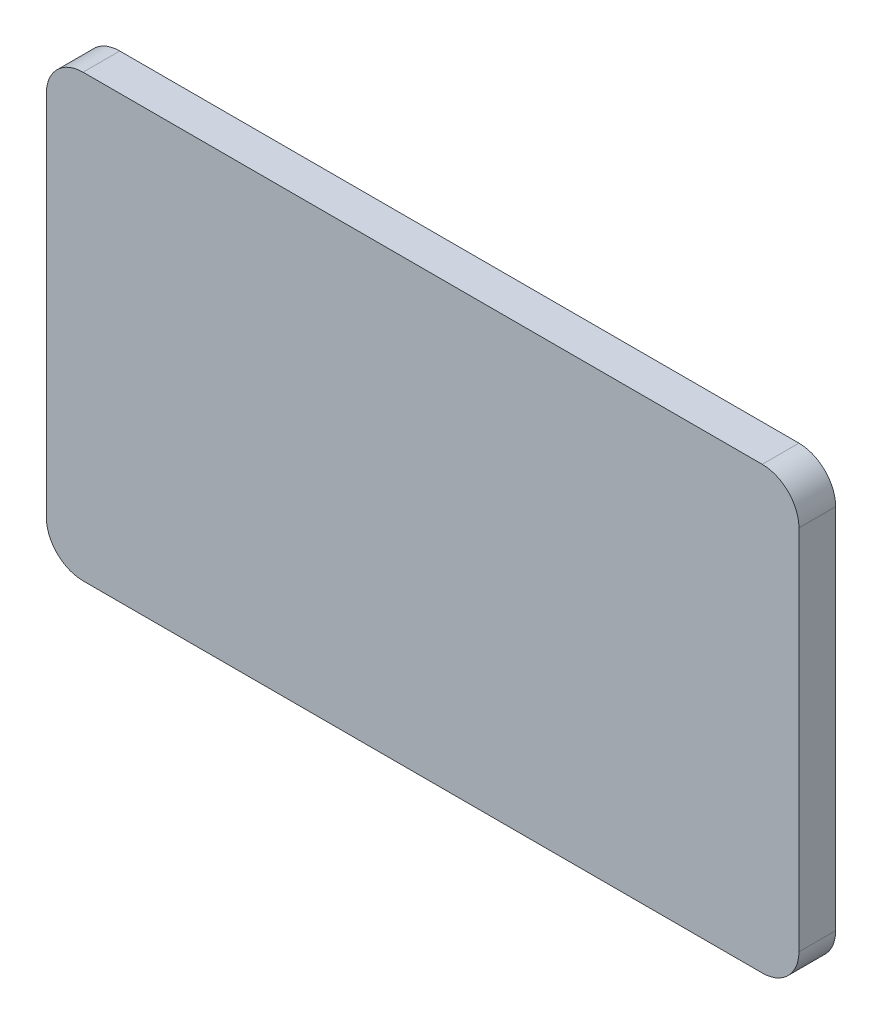
SolidWorks part; units mm, degrees
ref_plane "Front Plane" through (0, 0, 0) normal (0, 0, 1) x (1, 0, 0)
ref_plane "Top Plane" through (0, 0, 0) normal (0, 1, 0) x (1, 0, 0)
ref_plane "Right Plane" through (0, 0, 0) normal (1, 0, 0) x (0, 0, -1)
sketch "Sketch1" plane through (0, 0, 0) normal (0, 0, 1) x (1, 0, 0)
  line L1 (0, 0) -> (41, 0)
  line L2 (0, 0) -> (0, -24)
  line L3 (0, -24) -> (41, -24)
  line L4 (41, 0) -> (41, -24)
  dimension "D1" = 41
  dimension "D2" = 24
extrude "Boss-Extrude1" add sketch "Sketch1" along normal blind 2
fillet "Fillet1" radius 2 4 edges at (41, -24, 1) (0, -24, 1) (0, 0, 1) (41, 0, 1)
